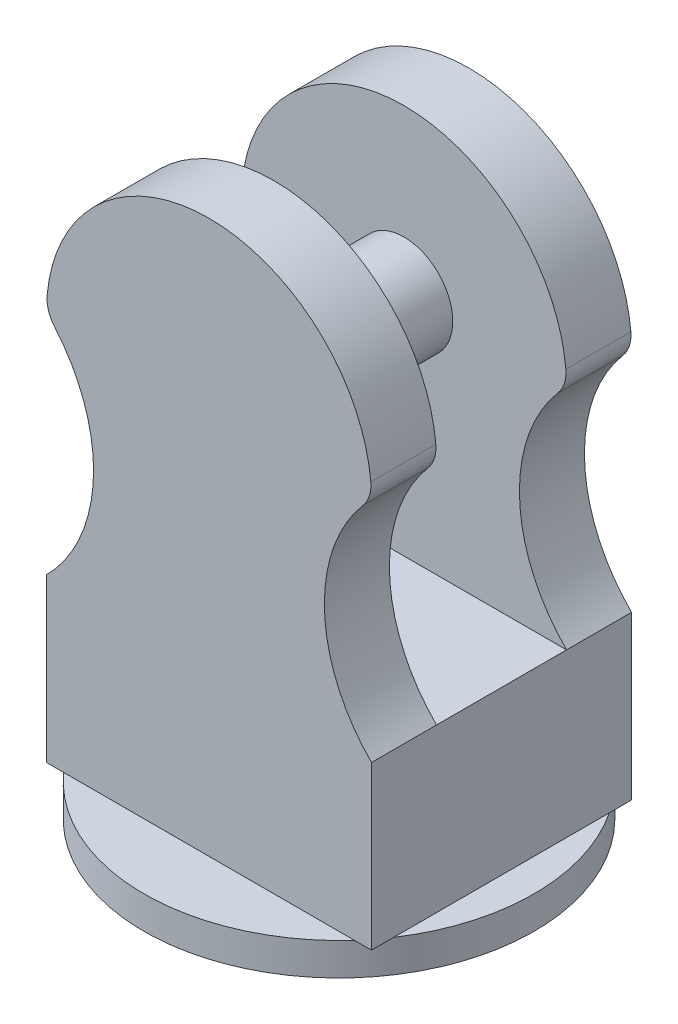
SolidWorks part; units mm, degrees
material "1060 Alloy"
ref_plane "Front Plane" through (0, 0, 0) normal (0, 0, 1) x (1, 0, 0)
ref_plane "Top Plane" through (0, 0, 0) normal (0, 1, 0) x (1, 0, 0)
ref_plane "Right Plane" through (0, 0, 0) normal (1, 0, 0) x (0, 0, -1)
sketch "Sketch1" plane through (0, 0, 0) normal (0, 0, 1) x (1, 0, 0)
  circle A0 centre (0, 0) radius 15
extrude "Boss-Extrude1" add sketch "Sketch1" along normal mid plane 80
sketch "Sketch2" plane through (0, 0, 40) normal (0, 0, 1) x (1, 0, 0)
  line L0 (0, 0) -> (0, -70) construction
  line L1 (50, 0) -> (50, -70)
  line L2 (-50, 0) -> (-50, -70)
  arc A0 (50, 0) -> (-50, 0) centre (0, 0) ccw
  arc A1 (-50, -70) -> (50, -70) centre (0, -70) ccw
  point P3 (0, -35)
  dimension "D1" = 50
  dimension "D2" = 70
extrude "Boss-Extrude2" add sketch "Sketch2" against normal blind 20
sketch "Sketch3" plane through (0, 0, -40) normal (0, 0, -1) x (-1, 0, 0)
  line L0 (0, 0) -> (0, -70) construction
  line L1 (50, 0) -> (50, -70)
  line L2 (-50, 0) -> (-50, -70)
  arc A0 (50, 0) -> (-50, 0) centre (0, 0) ccw
  arc A1 (-50, -70) -> (50, -70) centre (0, -70) ccw
  point P4 (0, -35)
extrude "Boss-Extrude3" add sketch "Sketch3" against normal blind 20
sketch "Sketch4" plane through (0, 0, -40) normal (0, 0, -1) x (-1, 0, 0)
  line L1 (-50, -70) -> (50, -70)
  line L2 (-50, -70) -> (-50, -120)
  line L3 (-50, -120) -> (50, -120)
  line L4 (50, -70) -> (50, -120)
extrude "Boss-Extrude4" add sketch "Sketch4" against normal blind 80
sketch "Sketch5" plane through (0, -120, 0) normal (0, -1, 0) x (1, 0, 0)
  circle A0 centre (0, 0) radius 60
extrude "Boss-Extrude5" add sketch "Sketch5" along normal blind 10
sketch "Sketch6" plane through (0, -130, 0) normal (0, -1, 0) x (1, 0, 0)
  circle A0 centre (0, 0) radius 15
extrude "Cut-Extrude1" cut sketch "Sketch6" against normal blind 10
sketch "Sketch7" plane through (0, 0, 40) normal (0, 0, 1) x (1, 0, 0)
  line L2 (-50, -70) -> (-50, 0)
  arc A1 (-50, 0) -> (-50, -70) centre (-85, -35) cw
extrude "Cut-Extrude2" cut sketch "Sketch7" against normal blind 90
sketch "Sketch8" plane through (0, 0, 40) normal (0, 0, 1) x (1, 0, 0)
  line L2 (50, -70) -> (50, 0)
  arc A1 (50, 0) -> (50, -70) centre (85, -35) ccw
extrude "Cut-Extrude3" cut sketch "Sketch8" against normal blind 90
fillet "Fillet2" radius 10 4 edges at (50, 0, -30) (50, 0, 30) (-50, 0, 30) (-50, 0, -30)
sketch "Sketch9" plane through (0, 0, 0) normal (0, 0, 1) x (1, 0, 0)
  line L0 (0, 0) -> (0, -130) construction
  line L1 (-15, -130) -> (15, -130) construction
  dimension "D1" = 130
